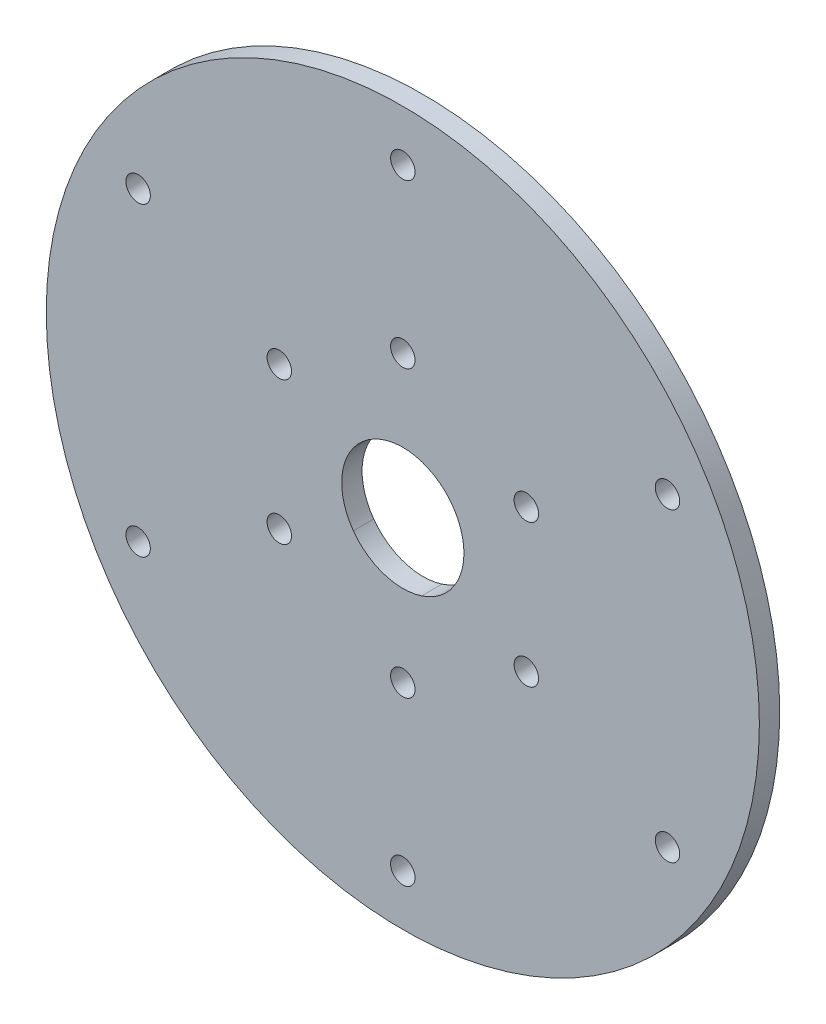
SolidWorks part; units mm, degrees
material "ASTM A36 Steel"
ref_plane "Front Plane" through (0, 0, 0) normal (0, 0, 1) x (1, 0, 0)
ref_plane "Top Plane" through (0, 0, 0) normal (0, 1, 0) x (1, 0, 0)
ref_plane "Right Plane" through (0, 0, 0) normal (1, 0, 0) x (0, 0, -1)
sketch "Sketch1" plane through (0, 0, 0) normal (0, 0, 1) x (1, 0, 0)
  circle A0 centre (0, 0) radius 175
  circle A1 centre (0, 0) radius 30
  circle A2 centre (-0.0007, 0.001) radius 30
  circle A8 centre (0, 0.0019) radius 30
  circle A11 centre (0.0011, 0.0015) radius 30
  circle A14 centre (0.0011, 0.0004) radius 30
  point P37 (0.0003, 0.001)
  dimension "D1" = 350
  dimension "D2" = 60
  dimension "D6" = 5
extrude "Boss-Extrude2" add sketch "Sketch1" along normal blind 10
sketch "Sketch2" plane through (0, 0, 0) normal (0, 0, -1) x (-1, 0, 0)
  circle A0 centre (0, 70) radius 6
  circle A1 centre (0, 150) radius 6
  dimension "D1" = 12
  dimension "D2" = 12
  dimension "D3" = 70
  dimension "D4" = 80
extrude "Cut-Extrude1" cut sketch "Sketch2" against normal through all
pattern_circular "CirPattern2" count 6 over 360 about axis through (0, 0, 0) along (0, 0, 1) of "Cut-Extrude1"
